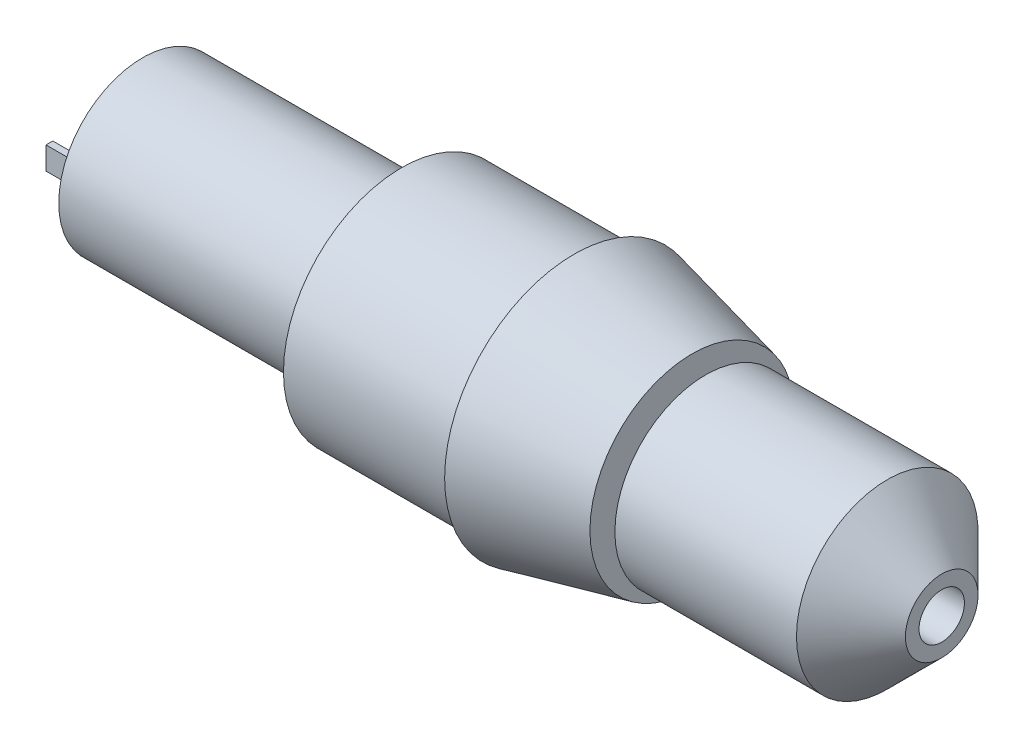
SolidWorks part; units mm, degrees
material "PF"
ref_plane "Спереди (XY)" through (0, 0, 0) normal (0, 0, 1) x (1, 0, 0)
ref_plane "Сверху (XZ)" through (0, 0, 0) normal (0, 1, 0) x (1, 0, 0)
ref_plane "Справа (ZY)" through (0, 0, 0) normal (1, 0, 0) x (0, 0, -1)
sketch "Эскиз1" plane through (0, 0, 0) normal (0, 0, 1) x (1, 0, 0)
  line L0 (0, 0) -> (0, 18.5)
  line L1 (0, 18.5) -> (57, 18.5)
  line L2 (57, 18.5) -> (57, 26)
  line L3 (57, 26) -> (95, 26)
  line L4 (95, 26) -> (95, 28.5)
  line L5 (95, 28.5) -> (121, 22.5)
  line L6 (121, 22.5) -> (121, 6)
  line L7 (121, 6) -> (124, 6)
  line L8 (124, 6) -> (124, 20)
  line L9 (124, 20) -> (164, 20)
  line L10 (164, 20) -> (176, 8)
  line L11 (176, 8) -> (176, 5)
  line L12 (176, 5) -> (166, 5)
  line L13 (166, 5) -> (166, 0)
  line L14 (-15.4049, 0) -> (175.0657, 0) construction
  line L15 (0, 0) -> (166, 0)
  dimension "D1" = 57
  dimension "D2" = 18.5
  dimension "D3" = 26
  dimension "D4" = 28.5
  dimension "D5" = 22.5
  dimension "D6" = 26
  dimension "D7" = 6
  dimension "D8" = 38
  dimension "D9" = 3
  dimension "D10" = 40
  dimension "D11" = 12
  dimension "D12" = 135
  dimension "D13" = 20
  dimension "D14" = 10
  dimension "D15" = 5
revolve "Повернуть1" add sketch "Эскиз1" angle 360 about L15
sketch "Эскиз2" plane through (0, 0, 0) normal (-1, 0, 0) x (0, 0, 1)
  line L0 (0, 16.4969) -> (0, -13.6978) construction
  line L1 (0, 0) -> (-13.4828, 0) construction
  line L2 (11.3067, -2.5) -> (9.8067, -2.5)
  line L3 (-11.3067, -2.5) -> (-9.8067, -2.5)
  line L4 (-11.3067, -2.5) -> (-11.3067, 2.5)
  line L5 (-11.3067, 2.5) -> (-9.8067, 2.5)
  line L6 (-9.8067, -2.5) -> (-9.8067, 2.5)
  line L7 (-11.3067, -2.5) -> (-9.8067, 2.5) construction
  line L8 (-11.3067, 2.5) -> (-9.8067, -2.5) construction
  line L9 (11.3067, -2.5) -> (11.3067, 2.5)
  line L10 (11.3067, 2.5) -> (9.8067, 2.5)
  line L11 (9.8067, -2.5) -> (9.8067, 2.5)
  point P5 (-10.5567, 0)
  dimension "D1" = 5
  dimension "D2" = 1.5
extrude "Бобышка-Вытянуть1" add sketch "Эскиз2" along normal blind 10
